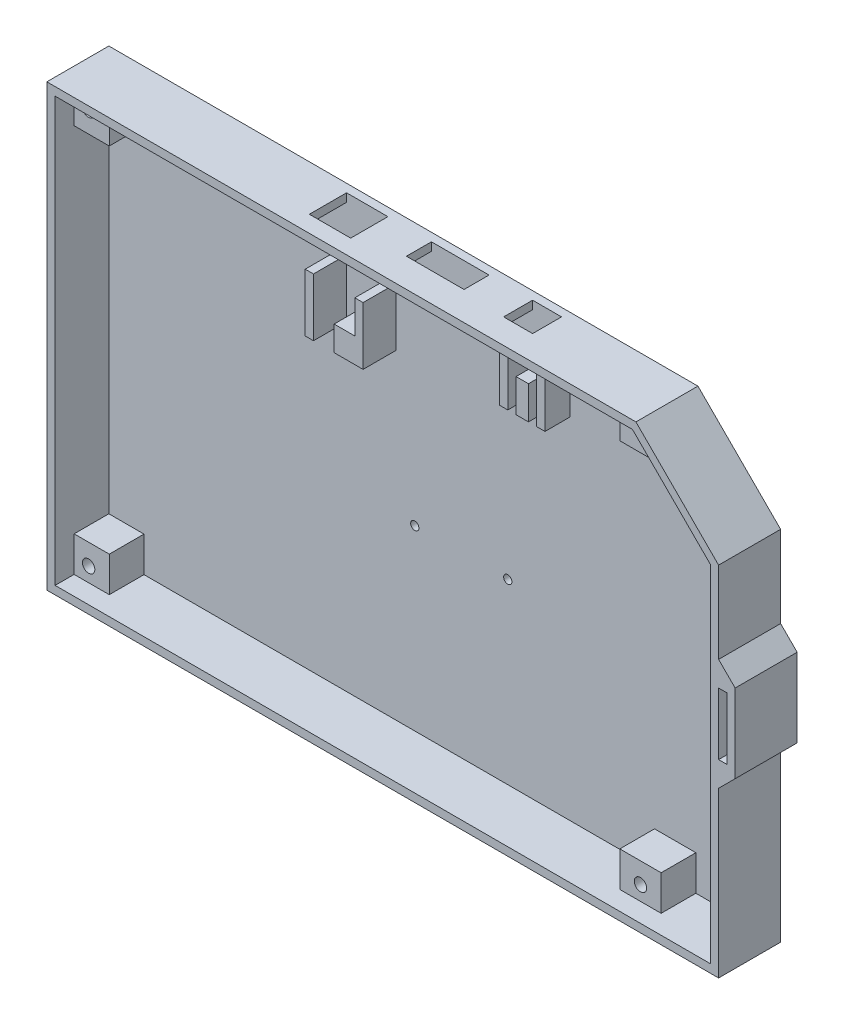
SolidWorks part; units mm, degrees
ref_plane "Front Plane" through (0, 0, 0) normal (0, 0, 1) x (1, 0, 0)
ref_plane "Top Plane" through (0, 0, 0) normal (0, 1, 0) x (1, 0, 0)
ref_plane "Right Plane" through (0, 0, 0) normal (1, 0, 0) x (0, 0, -1)
sketch "Sketch1" plane through (0, 0, 0) normal (0, 0, 1) x (1, 0, 0)
  line L10 (90.25, -53.25) -> (-72.25, -53.25) construction
  line L11 (90.25, 33.25) -> (90.25, -53.25) construction
  line L12 (70.25, 53.25) -> (90.25, 33.25) construction
  line L13 (70.25, 53.25) -> (-72.25, 53.25) construction
  line L14 (-72.25, 53.25) -> (-72.25, -53.25) construction
  line L15 (90.25, -53.25) -> (-72.25, -53.25)
  line L16 (90.25, 33.25) -> (90.25, -53.25)
  line L17 (70.25, 53.25) -> (90.25, 33.25)
  line L18 (70.25, 53.25) -> (-72.25, 53.25)
  line L19 (-72.25, 53.25) -> (-72.25, -53.25)
  circle A0 centre (3.75, -8.25) radius 1 construction
  circle A1 centre (26.25, -8.25) radius 1 construction
  circle A2 centre (26.25, 48.75) radius 1 construction
  circle A3 centre (3.75, 48.75) radius 1 construction
  circle A4 centre (3.75, -8.25) radius 1
  circle A5 centre (26.25, -8.25) radius 1
  circle A6 centre (26.25, 48.75) radius 1
  circle A7 centre (3.75, 48.75) radius 1
extrude "Boss-Extrude1" add sketch "Sketch1" against normal blind 2 contours L18 L19 L15 L16 L17 A7 A6 A5 A4
sketch "Sketch3" plane through (0, 0, 0) normal (0, 0, 1) x (1, 0, 0)
  line L0 (70.25, 53.25) -> (90.25, 33.25) construction
  line L9 (61.75, 52.75) -> (70.75, 52.75)
  line L10 (61.75, 52.75) -> (61.75, 42.75)
  line L11 (61.75, 42.75) -> (71.75, 42.75)
  line L12 (71.75, 51.75) -> (71.75, 42.75)
  line L13 (61.75, 52.75) -> (71.75, 42.75) construction
  line L14 (61.75, 42.75) -> (71.75, 52.75) construction
  line L15 (70.75, 52.75) -> (71.75, 51.75)
  line L16 (70.75, 52.75) -> (71.75, 52.75) construction
  line L17 (61.75, -52.75) -> (71.75, -52.75)
  line L18 (61.75, -52.75) -> (61.75, -42.75)
  line L19 (61.75, -42.75) -> (71.75, -42.75)
  line L20 (71.75, -52.75) -> (71.75, -42.75)
  line L21 (61.75, -52.75) -> (71.75, -42.75) construction
  line L22 (61.75, -42.75) -> (71.75, -52.75) construction
  line L23 (71.75, 52.75) -> (71.75, 51.75) construction
  line L26 (-71.75, 42.75) -> (-61.75, 42.75)
  line L27 (-71.75, 42.75) -> (-71.75, 52.75)
  line L28 (-71.75, 52.75) -> (-61.75, 52.75)
  line L29 (-61.75, 42.75) -> (-61.75, 52.75)
  line L30 (-71.75, 42.75) -> (-61.75, 52.75) construction
  line L31 (-71.75, 52.75) -> (-61.75, 42.75) construction
  line L32 (-71.75, -42.75) -> (-61.75, -42.75)
  line L33 (-71.75, -42.75) -> (-71.75, -52.75)
  line L34 (-71.75, -52.75) -> (-61.75, -52.75)
  line L35 (-61.75, -42.75) -> (-61.75, -52.75)
  line L36 (-71.75, -42.75) -> (-61.75, -52.75) construction
  line L37 (-71.75, -52.75) -> (-61.75, -42.75) construction
  circle A0 centre (66.75, 47.75) radius 1.5 construction
  circle A1 centre (66.75, -47.75) radius 1.5 construction
  circle A2 centre (-66.75, -47.75) radius 1.5 construction
  circle A3 centre (-66.75, 47.75) radius 1.5 construction
  circle A4 centre (66.75, 47.75) radius 1.5
  circle A5 centre (66.75, -47.75) radius 1.5
  circle A6 centre (-66.75, -47.75) radius 1.5
  circle A7 centre (-66.75, 47.75) radius 1.5
  dimension "D1" = 10
  dimension "D2" = 10
  dimension "D3" = 10
  dimension "D4" = 10
  dimension "D5" = 10
  dimension "D6" = 10
  dimension "D7" = 10
  dimension "D8" = 10
extrude "Boss-Extrude2" add sketch "Sketch3" along normal up to surface (8.4 mm away) contours A7 | A4
sketch "Sketch5" plane through (0, 0, 0) normal (0, 0, 1) x (1, 0, 0)
  line L10 (90.25, 33.25) -> (90.25, -53.25)
  line L11 (90.25, -53.25) -> (-72.25, -53.25)
  line L12 (-72.25, 53.25) -> (-72.25, -53.25)
  line L13 (70.25, 53.25) -> (39.25, 53.25)
  line L14 (70.25, 53.25) -> (90.25, 33.25)
  line L15 (69.4216, 51.25) -> (39.25, 51.25)
  line L16 (-70.25, 51.25) -> (-70.25, -51.25)
  line L17 (88.25, -51.25) -> (-70.25, -51.25)
  line L18 (88.25, 32.4216) -> (88.25, -51.25)
  line L19 (69.4216, 51.25) -> (88.25, 32.4216)
  line L20 (7.7822, 53.25) -> (7.7822, 51.25)
  line L21 (21.7178, 53.25) -> (21.7178, 51.25)
  line L22 (7.7822, 53.25) -> (-2.75, 53.25)
  line L23 (70.25, 53.25) -> (-72.25, 53.25) construction
  line L24 (7.7822, 51.25) -> (-2.75, 51.25)
  line L25 (69.4216, 51.25) -> (-70.25, 51.25) construction
  line L26 (14.75, 51.75) -> (14.75, 53.25) construction
  line L27 (10.25, 51.75) -> (19.25, 51.75) construction
  line L28 (70.25, 53.25) -> (-72.25, 53.25) construction
  line L29 (90.25, 33.25) -> (90.25, -53.25) construction
  line L30 (90.25, -53.25) -> (-72.25, -53.25) construction
  line L31 (-72.25, 53.25) -> (-72.25, -53.25) construction
  line L32 (-12.75, 51.25) -> (-12.75, 53.25)
  line L33 (-2.75, 51.25) -> (-2.75, 53.25)
  line L34 (-12.75, 53.25) -> (-72.25, 53.25)
  line L35 (-12.75, 51.25) -> (-70.25, 51.25)
  line L36 (-7.75, 45.75) -> (-7.75, 53.25) construction
  line L37 (-5.75, 45.75) -> (-9.75, 45.75) construction
  line L39 (32.25, 51.25) -> (32.25, 53.25)
  line L40 (39.25, 51.25) -> (39.25, 53.25)
  line L41 (32.25, 51.25) -> (21.7178, 51.25)
  line L42 (32.25, 53.25) -> (21.7178, 53.25)
  line L43 (35.75, 45.25) -> (35.75, 53.25) construction
  line L44 (32.75, 45.25) -> (38.75, 45.25) construction
  dimension "D2" = 13.9357
  dimension "D3" = 10
  dimension "D4" = 7
  dimension "D1" = 2
extrude "Boss-Extrude3" add sketch "Sketch5" along normal up to surface (13 mm away)
sketch "Sketch6" plane through (0, 53.25, 0) normal (0, 1, 0) x (1, 0, 0)
  line L0 (-12.75, -13) -> (-12.75, 0) construction
  line L1 (-2.75, -13) -> (-2.75, 0) construction
  line L2 (7.7822, -13) -> (7.7822, 0) construction
  line L3 (21.7178, -13) -> (21.7178, 0) construction
  line L4 (32.25, -13) -> (32.25, 0) construction
  line L5 (39.25, -13) -> (39.25, 0) construction
  line L6 (-12.75, -13) -> (-12.75, -9)
  line L7 (-2.75, -13) -> (-2.75, -9)
  line L8 (7.7822, -13) -> (7.7822, -6.05)
  line L9 (21.7178, -13) -> (21.7178, -6.05)
  line L10 (32.25, -13) -> (32.25, -7)
  line L11 (39.25, -13) -> (39.25, -7)
  line L12 (39.25, -7) -> (32.25, -7)
  line L13 (32.75, -6) -> (38.75, -6) construction
  line L14 (21.7178, -6.05) -> (7.7822, -6.05)
  line L15 (-2.75, -9) -> (-12.75, -9)
  line L16 (-11.75, -8) -> (-3.75, -8) construction
  line L17 (10.25, -5.05) -> (19.25, -5.05) construction
  line L18 (39.25, -13) -> (32.25, -13)
  line L19 (21.7178, -13) -> (7.7822, -13)
  line L20 (-2.75, -13) -> (-12.75, -13)
  dimension "D1" = 1
  dimension "D2" = 1
  dimension "D3" = 1
extrude "Boss-Extrude4" add sketch "Sketch6" against normal up to surface (2 mm away) up to face at (26.9839, 51.25, 6.5)
sketch "Sketch7" plane through (0, 0, 0) normal (0, 0, 1) x (1, 0, 0)
  line L0 (37.25, 36.25) -> (37.25, 41.25) construction
  line L1 (34.25, 41.25) -> (37.25, 41.25)
  line L2 (34.25, 41.25) -> (34.25, 33.25)
  line L3 (34.25, 33.25) -> (37.25, 33.25)
  line L4 (37.25, 41.25) -> (37.25, 33.25)
  line L5 (32.25, 51.25) -> (32.25, 33.25) construction
  line L6 (32.25, 33.25) -> (30.25, 33.25)
  line L7 (30.25, 33.25) -> (30.25, 51.25) construction
  line L8 (21.7178, 51.25) -> (32.25, 51.25) construction
  line L9 (41.25, 51.25) -> (39.25, 51.25) construction
  line L10 (30.25, 51.25) -> (32.25, 51.25) construction
  line L11 (35.75, 41.25) -> (35.75, 33.25) construction
  line L12 (41.25, 33.25) -> (41.25, 51.25) construction
  line L13 (39.25, 33.25) -> (41.25, 33.25)
  line L14 (39.25, 51.25) -> (39.25, 33.25) construction
  line L15 (30.25, 45.25) -> (32.25, 45.25)
  line L16 (32.75, 45.25) -> (38.75, 45.25) construction
  line L17 (30.25, 45.25) -> (30.25, 33.25)
  line L18 (32.25, 33.25) -> (32.25, 45.25)
  line L19 (39.25, 33.25) -> (39.25, 45.25)
  line L20 (41.25, 45.25) -> (41.25, 33.25)
  line L21 (39.25, 45.25) -> (41.25, 45.25)
  dimension "D1" = 8
  dimension "D2" = 18
  dimension "D3" = 2
extrude "Boss-Extrude5" add sketch "Sketch7" along normal blind 6
sketch "Sketch8" plane through (0, 0, 0) normal (0, 0, 1) x (1, 0, 0)
  line L0 (-12.75, 51.25) -> (-12.75, 26.25) construction
  line L1 (-7.75, 53.25) -> (-7.75, 26.25) construction
  line L2 (-2.75, 53.25) -> (-12.75, 53.25) construction
  line L3 (-12.75, 26.25) -> (-14.75, 26.25)
  line L4 (-14.75, 26.25) -> (-14.75, 51.25) construction
  line L5 (-61.75, 51.25) -> (-12.75, 51.25) construction
  line L6 (-14.75, 51.25) -> (-12.75, 51.25) construction
  line L7 (-7.75, 26.25) -> (-7.75, 32.25)
  line L8 (-7.75, 32.25) -> (-3.75, 32.25)
  line L10 (-2.75, 26.25) -> (-7.75, 26.25)
  line L11 (-0.75, 51.25) -> (-2.75, 51.25) construction
  line L12 (-0.75, 26.25) -> (-0.75, 51.25) construction
  line L13 (-2.75, 26.25) -> (-0.75, 26.25)
  line L14 (-2.75, 51.25) -> (-2.75, 32.25) construction
  line L15 (-3.75, 32.25) -> (-2.75, 32.25)
  line L16 (-14.75, 40.25) -> (-12.75, 40.25)
  line L17 (-11.75, 40.25) -> (-3.75, 40.25) construction
  line L18 (-14.75, 40.25) -> (-14.75, 26.25)
  line L19 (-12.75, 26.25) -> (-12.75, 40.25)
  line L20 (-2.75, 40.25) -> (-2.75, 32.25)
  line L21 (-0.75, 40.25) -> (-0.75, 26.25)
  line L22 (-2.75, 40.25) -> (-0.75, 40.25)
  dimension "D1" = 25
  dimension "D2" = 2
extrude "Boss-Extrude6" add sketch "Sketch8" along normal blind 8
sketch "Sketch9" plane through (0, 0, -2) normal (0, 0, -1) x (-1, 0, 0)
  line L0 (-70.25, 53.25) -> (72.25, 53.25) construction
  line L1 (-90.25, 53.25) -> (-90.25, -53.25) construction
  line L2 (-90.25, -53.25) -> (-90.25, 33.25) construction
  line L3 (-94.25, -9.5) -> (-88.25, -9.5) construction
  line L5 (-87.6982, 9.5691) -> (-87.6982, -9.5691) construction
  line L7 (-92.25, 7.5) -> (-92.25, -7.5) construction
  line L8 (-87.6982, 9.5691) -> (-92.25, -7.5) construction
  line L9 (-87.6982, -9.5691) -> (-92.25, 7.5) construction
  line L10 (-92.25, 7.5) -> (-90.25, 7.5)
  line L11 (-92.25, 7.5) -> (-92.25, -7.5)
  line L12 (-92.25, -7.5) -> (-90.25, -7.5)
  line L13 (-90.25, 7.5) -> (-90.25, -7.5) construction
  line L14 (-88.25, 9.5) -> (-88.25, -9.5) construction
  line L15 (-94.25, 9.5) -> (-88.25, 9.5) construction
  line L16 (-94.25, 9.5) -> (-94.25, -9.5)
  line L17 (-94.25, 9.5) -> (-90.25, 13.5)
  line L18 (-90.25, 13.5) -> (-90.25, 9.5)
  line L19 (-94.25, -9.5) -> (-90.25, -13.5)
  line L20 (-90.25, -13.5) -> (-90.25, -9.5)
  line L21 (-90.25, 9.5) -> (-90.25, 7.5)
  line L22 (-90.25, -7.5) -> (-90.25, -9.5)
  point P0 (-90.25, 0)
  point P22 (-87.6982, 0)
  dimension "D1" = 5
  dimension "D2" = 15
  dimension "D4" = 45
  dimension "D5" = 45
  dimension "D6" = 2
  dimension "D3" = 2
extrude "Boss-Extrude7" add sketch "Sketch9" against normal up to surface (15 mm away) up to face at (21.0843, 6.4843, 13)
